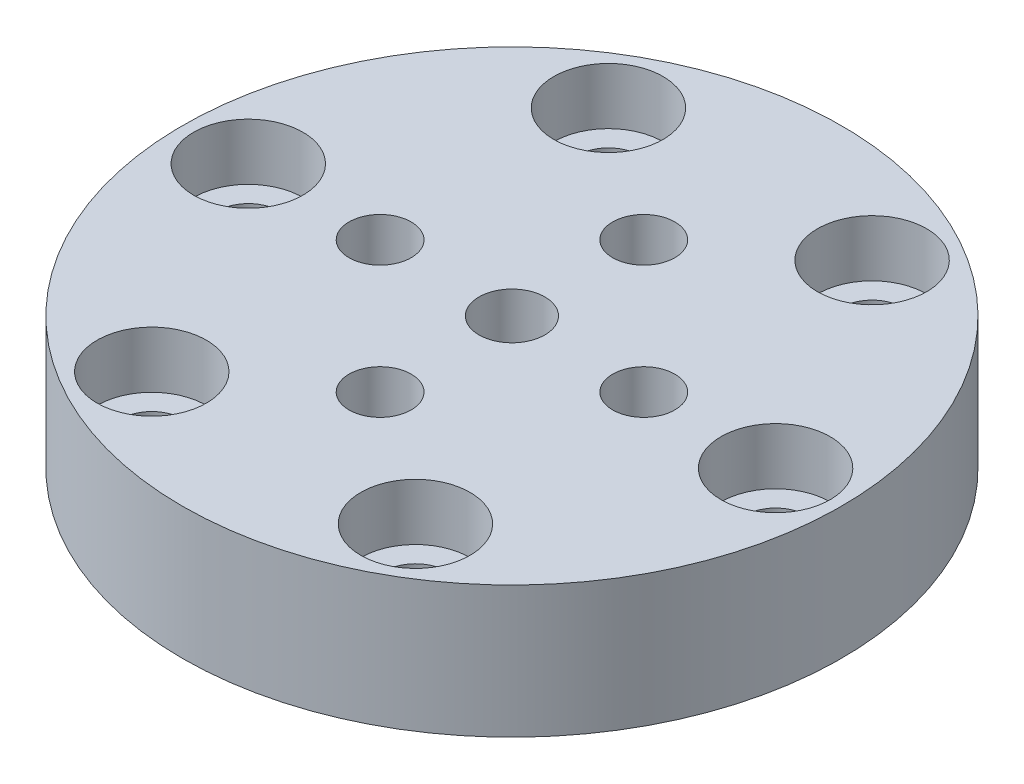
SolidWorks part; units mm, degrees
ref_plane "Front Plane" through (0, 0, 0) normal (0, 0, 1) x (1, 0, 0)
ref_plane "Top Plane" through (0, 0, 0) normal (0, 1, 0) x (1, 0, 0)
ref_plane "Right Plane" through (0, 0, 0) normal (1, 0, 0) x (0, 0, -1)
sketch "草图1" plane through (0, 0, 0) normal (0, 1, 0) x (1, 0, 0)
  circle A0 centre (0, 0) radius 17.5
  circle A1 centre (0, 0) radius 14 construction
  circle A2 centre (-14, 0) radius 1.65
  circle A3 centre (-7, 12.1244) radius 1.65
  circle A4 centre (7, 12.1244) radius 1.65
  circle A5 centre (14, 0) radius 1.65
  circle A6 centre (7, -12.1244) radius 1.65
  circle A7 centre (-7, -12.1244) radius 1.65
  circle A8 centre (0, 0) radius 1.75
  circle A9 centre (0, 0) radius 7
  circle A10 centre (7, 0) radius 1.65
  circle A11 centre (0, -7) radius 1.65
  circle A12 centre (-7, 0) radius 1.65
  circle A13 centre (0, 7) radius 1.65
  point P18 (0, 0)
  point P30 (0, 0)
  dimension "D1" = 35
  dimension "D2" = 28
  dimension "D3" = 3.3
  dimension "D5" = 3.5
  dimension "D6" = 14
  dimension "D7" = 3.3
  dimension "D4" = 6
  dimension "D8" = 4
extrude "凸台-拉伸1" add sketch "草图1" along normal blind 7 contours A0 A13 A9 A10 A11 A12 A7 A6 A5 A4 A3 A2 | A13 A9 A12 A11 A10 A8
sketch "草图2" plane through (0, 7, 0) normal (0, 1, 0) x (1, 0, 0)
  circle A0 centre (-14, 0) radius 2.9
  circle A1 centre (-7, 12.1244) radius 2.9
  circle A2 centre (7, 12.1244) radius 2.9
  circle A3 centre (14, 0) radius 2.9
  circle A4 centre (7, -12.1244) radius 2.9
  circle A5 centre (-7, -12.1244) radius 2.9
  point P15 (0, 0)
  dimension "D1" = 5.8
  dimension "D2" = 6
extrude "切除-拉伸1" cut sketch "草图2" against normal blind 3
